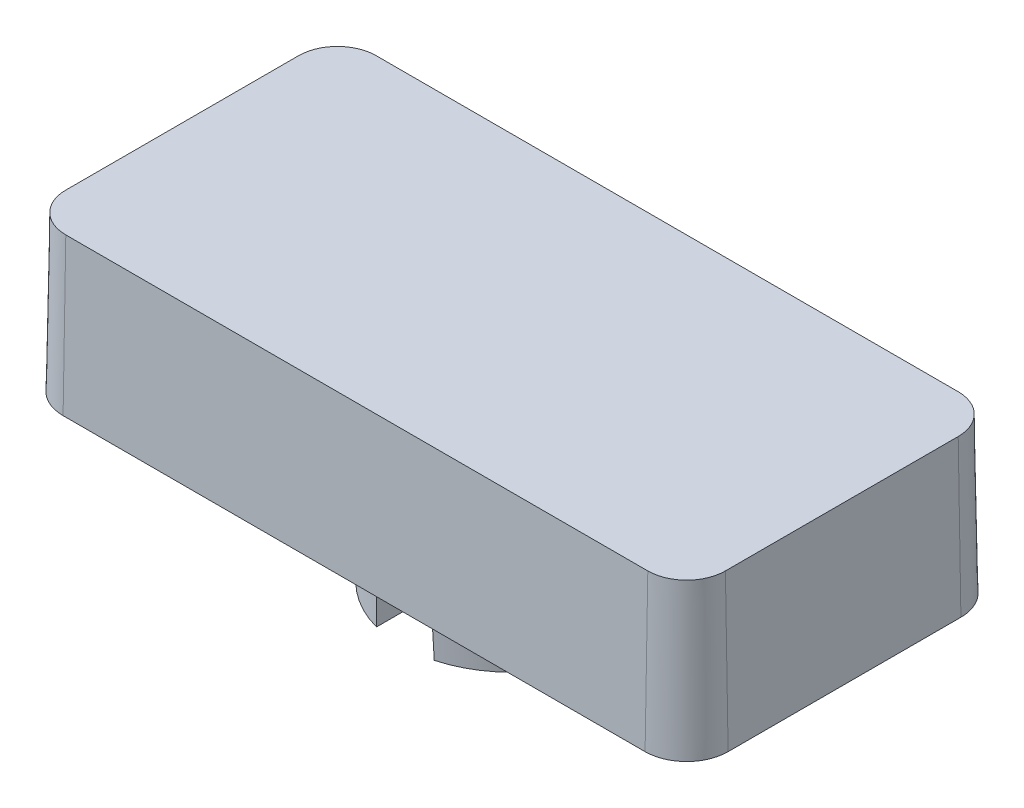
SolidWorks part; units mm, degrees
ref_plane "Front Plane" through (0, 0, 0) normal (0, 0, 1) x (1, 0, 0)
ref_plane "Top Plane" through (0, 0, 0) normal (0, 1, 0) x (1, 0, 0)
ref_plane "Right Plane" through (0, 0, 0) normal (1, 0, 0) x (0, 0, -1)
sketch "Sketch1" plane through (0, 0, 0) normal (0, 1, 0) x (1, 0, 0)
  line L1 (-7.5, -4) -> (7.5, -4)
  line L2 (-8.5, -3) -> (-8.5, 3)
  line L3 (-7.5, 4) -> (7.5, 4)
  line L4 (8.5, -3) -> (8.5, 3)
  line L5 (-8.5, -4) -> (8.5, 4) construction
  line L6 (-8.5, 4) -> (8.5, -4) construction
  arc A0 (-8.5, 3) -> (-7.5, 4) centre (-7.5, 3) cw
  arc A1 (8.5, 3) -> (7.5, 4) centre (7.5, 3) ccw
  arc A2 (8.5, -3) -> (7.5, -4) centre (7.5, -3) cw
  arc A3 (-7.5, -4) -> (-8.5, -3) centre (-7.5, -3) cw
  point P0 (0, 0)
  dimension "D3" = 1
  dimension "D1" = 17
  dimension "D2" = 8
extrude "Boss-Extrude1" add sketch "Sketch1" against normal blind 4 draft 1 draft outward yes
shell "Shell1" thickness 0.5
sketch "Sketch2" plane through (0, -0.5, 0) normal (0, -1, 0) x (1, 0, 0)
  line L0 (-0.6, 2.9308) -> (-0.6, 0.6)
  line L1 (-2.9308, 0.6) -> (-0.6, 0.6)
  line L2 (0, -55) -> (0, 55) construction
  line L3 (2.2, 0) -> (-2.2, 0) construction
  line L4 (-2.9308, -0.6) -> (-0.6, -0.6)
  line L5 (0.6, 2.9308) -> (0.6, 0.6)
  line L6 (-0.6, -0.6) -> (-0.6, -2.9308)
  line L7 (0.6, -0.6) -> (0.6, -2.9308)
  line L8 (0.6, -0.6) -> (2.9308, -0.6)
  line L9 (0.6, 0.6) -> (2.9308, 0.6)
  arc A0 (-2.9308, -0.6) -> (-0.6, -2.9308) centre (0, 0) ccw
  arc A1 (2.9308, 0.6) -> (0.6, 2.9308) centre (0, 0) ccw
  arc A2 (-0.6, 2.9308) -> (-2.9308, 0.6) centre (0, 0) ccw
  arc A3 (0.6, -2.9308) -> (2.9308, -0.6) centre (0, 0) ccw
  dimension "D1" = 0.6
  dimension "D2" = 0.6
extrude "Boss-Extrude2" add sketch "Sketch2" along normal blind 5.5 draft 1.5
